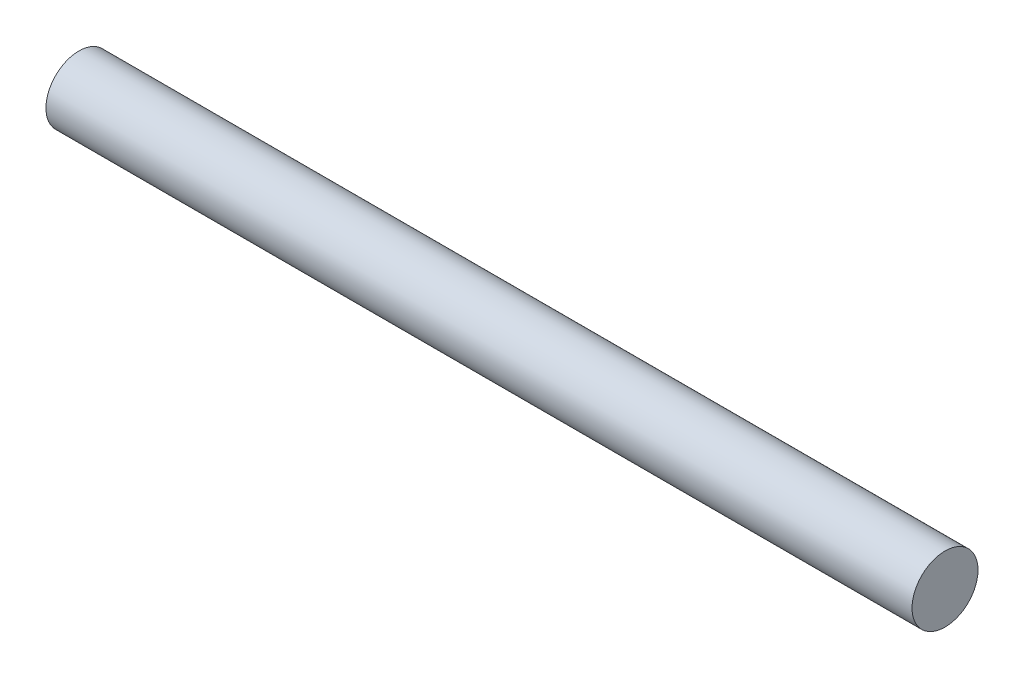
SolidWorks part; units mm, degrees
ref_plane "前视基准面" through (0, 0, 0) normal (0, 0, 1) x (1, 0, 0)
ref_plane "上视基准面" through (0, 0, 0) normal (0, 1, 0) x (1, 0, 0)
ref_plane "右视基准面" through (0, 0, 0) normal (1, 0, 0) x (0, 0, -1)
sketch "草图1" plane through (0, 0, 0) normal (1, 0, 0) x (0, 0, -1)
  circle A0 centre (0, 0) radius 4
  dimension "D1" = 8
extrude "凸台-拉伸1" add sketch "草图1" along normal blind 105
